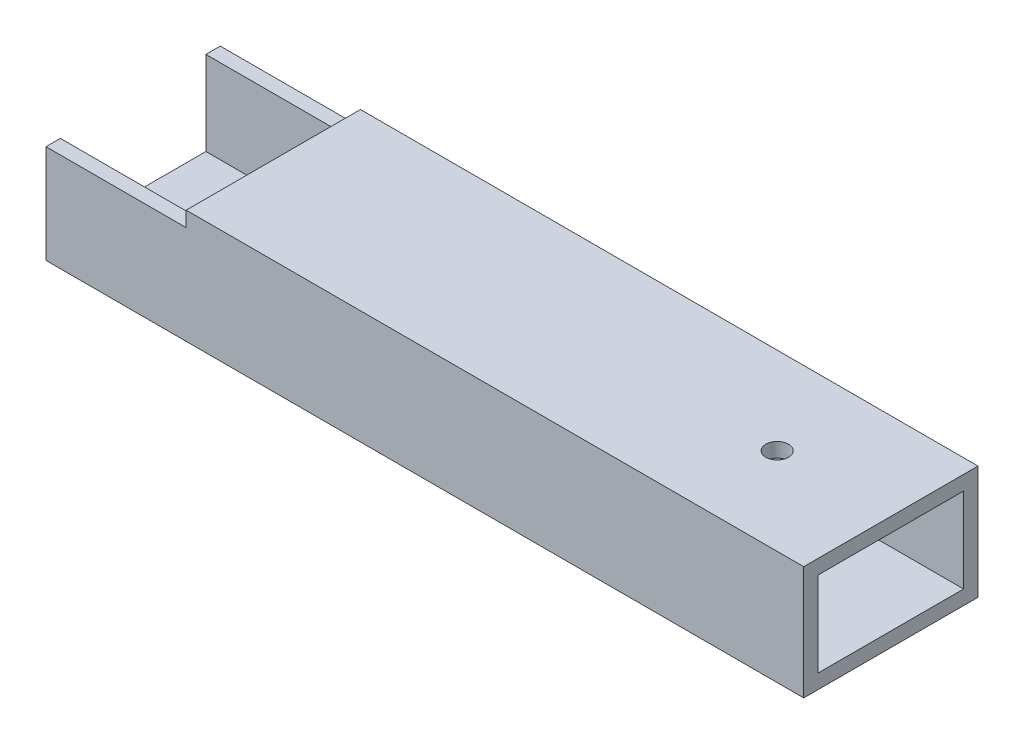
SolidWorks part; units mm, degrees
ref_plane "前视基准面" through (0, 0, 0) normal (0, 0, 1) x (1, 0, 0)
ref_plane "上视基准面" through (0, 0, 0) normal (0, 1, 0) x (1, 0, 0)
ref_plane "右视基准面" through (0, 0, 0) normal (1, 0, 0) x (0, 0, -1)
other "Configuration Table"
sketch "草图1" plane through (0, 0, 0) normal (0, 1, 0) x (1, 0, 0)
  line L1 (-50, 9.5) -> (-50, -9.5)
  line L3 (-50, 9.5) -> (50, 9.5)
  line L7 (-50, -9.5) -> (50, -9.5)
  line L9 (50, 9.5) -> (50, -9.5)
  circle A0 centre (-35, 0) radius 1.5
  circle A1 centre (35, 0) radius 1.5
extrude "凸台-拉伸2" add sketch "草图1" along normal blind 2 contours A0 | A1 | L9 L7 L1 L3
sketch "草图2" plane through (0, 2, 0) normal (0, 1, 0) x (1, 0, 0)
  line L1 (-50, 9.5) -> (50, 9.5)
  line L2 (-50, 9.5) -> (-50, 11.5)
  line L3 (-50, 11.5) -> (50, 11.5)
  line L4 (50, 9.5) -> (50, 11.5)
  line L5 (-50, -9.5) -> (50, -9.5)
  line L6 (-50, -9.5) -> (-50, -11.5)
  line L7 (-50, -11.5) -> (50, -11.5)
  line L8 (50, -9.5) -> (50, -11.5)
  line M8 (-50, -9.5) -> (50, -9.5)
extrude "凸台-拉伸3" add sketch "草图2" against normal blind 15 contours L8 L6 L7 M8 | L2 L1 L4 L3
sketch "草图3" plane through (0, -13, 0) normal (0, -1, 0) x (-1, 0, 0)
  line L1 (50, -9.5) -> (-50, -9.5)
  line L2 (50, -9.5) -> (50, 9.5)
  line L3 (50, 9.5) -> (-50, 9.5)
  line L4 (-50, -9.5) -> (-50, 9.5)
  circle A0 centre (35, 0) radius 1.5
  circle A1 centre (-35, 0) radius 1.5
extrude "凸台-拉伸5" add sketch "草图3" against normal blind 2
sketch "草图5" plane through (0, 2, 0) normal (0, 1, 0) x (1, 0, 0)
  line L0 (-36.5, 0) -> (-38.5, 0)
  line L1 (-38.5, 0) -> (-38.5, -11.5)
  line L2 (-50, -11.5) -> (50, -11.5) construction
  line L4 (-50, 11.5) -> (-38.5, 11.5)
  line L5 (-50, 11.5) -> (-50, -11.5)
  line L6 (-50, -11.5) -> (-38.5, -11.5)
  line L7 (-38.5, 11.5) -> (-38.5, -11.5)
  circle A0 centre (-35, 0) radius 1.5 construction
  line M7 (50, 11.5) -> (-50, 11.5)
  line M8 (-50, 11.5) -> (-50, -11.5)
  line M9 (-50, -11.5) -> (50, -11.5)
extrude "切除-拉伸1" cut sketch "草图5" against normal blind 2 contours L7 L1 M7 M8 M9
sketch "草图7" plane through (50, 0, 0) normal (1, 0, 0) x (0, 0, -1)
  line L0 (9.5, -11) -> (9.6, -11)
  line L1 (9.6, -11) -> (9.6, -11.1)
  line L2 (-9.5, 0) -> (-9.5, 0.1)
  line L3 (-9.5, 0.1) -> (-9.6, 0.1)
  line L5 (-9.6, 0.1) -> (9.6, 0.1)
  line L6 (-9.6, 0.1) -> (-9.6, -11.1)
  line L7 (-9.6, -11.1) -> (9.6, -11.1)
  line L8 (9.6, 0.1) -> (9.6, -11.1)
  line M9 (9.5, -11) -> (-9.5, -11)
  line M10 (-9.5, -11) -> (-9.5, 0)
  line M11 (-9.5, 0) -> (9.5, 0)
  line M12 (9.5, 0) -> (9.5, -11)
extrude "切除-拉伸2" cut sketch "草图7" against normal blind 100 contours L8 L5 L2 L0 M11 M12 | M9 M12 M11 M10 | L6 L7 L1 L0 L2 L3 M9 M10
sketch "草图8" plane through (0, 2, 0) normal (0, 1, 0) x (1, 0, 0)
  line L0 (-33.5, 0) -> (-31.5, 0)
  line L1 (-31.5, 0) -> (-31.5, -11.5)
  line L2 (-38.5, -11.5) -> (50, -11.5) construction
  line L3 (-31.5, 0) -> (-31.5, 11.5)
  line L4 (-38.5, 11.5) -> (50, 11.5) construction
  line L6 (-31.5, 11.5) -> (-38.5, 11.5)
  line L7 (-31.5, 11.5) -> (-31.5, -11.5)
  line L8 (-31.5, -11.5) -> (-38.5, -11.5)
  line L9 (-38.5, 11.5) -> (-38.5, -11.5)
  circle A0 centre (-35, 0) radius 1.5 construction
extrude "切除-拉伸3" cut sketch "草图8" against normal blind 2
